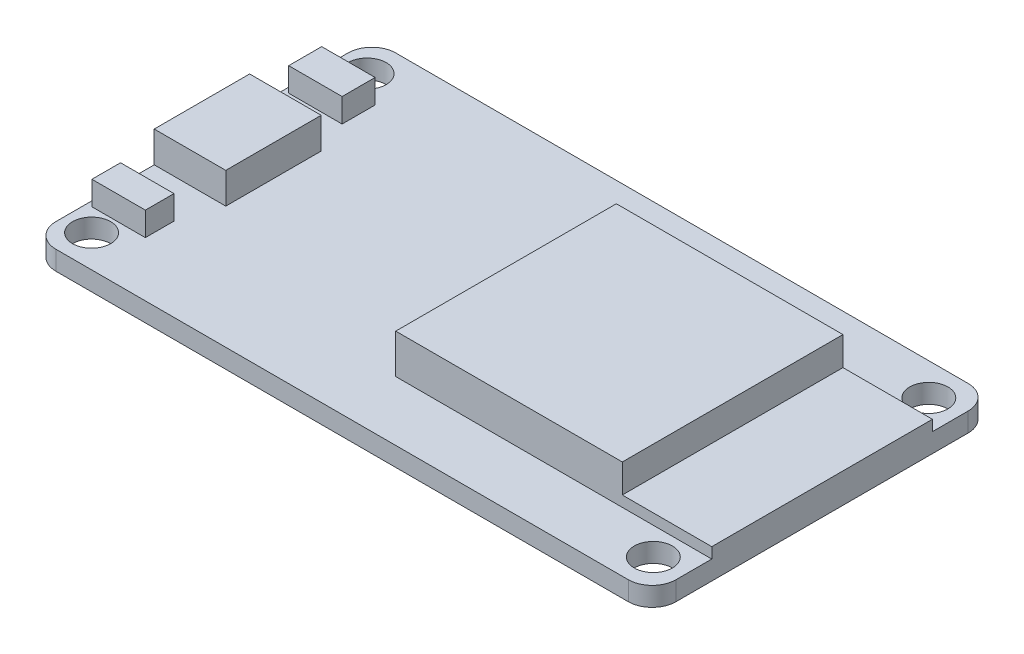
SolidWorks part; units mm, degrees
ref_plane "Front Plane" through (0, 0, 0) normal (0, 0, 1) x (1, 0, 0)
ref_plane "Top Plane" through (0, 0, 0) normal (0, 1, 0) x (1, 0, 0)
ref_plane "Right Plane" through (0, 0, 0) normal (1, 0, 0) x (0, 0, -1)
sketch "Sketch1" plane through (0, 0, 0) normal (0, 1, 0) x (1, 0, 0)
  line L1 (26, -14.25) -> (-26, -14.25)
  line L2 (26, -14.25) -> (26, 14.25)
  line L3 (26, 14.25) -> (-26, 14.25)
  line L4 (-26, -14.25) -> (-26, 14.25)
  line L5 (26, -14.25) -> (-26, 14.25) construction
  line L6 (26, 14.25) -> (-26, -14.25) construction
  line L7 (-23.7, -11.55) -> (23.4, -11.55) construction
  line L8 (-23.7, -11.55) -> (-23.7, 11.55) construction
  line L9 (-23.7, 11.55) -> (23.4, 11.55) construction
  line L10 (23.4, -11.55) -> (23.4, 11.55) construction
  line L11 (-23.7, -11.55) -> (23.4, 11.55) construction
  line L12 (-23.7, 11.55) -> (23.4, -11.55) construction
  circle A0 centre (-23.7, 11.55) radius 1.6
  circle A1 centre (-23.7, -11.55) radius 1.6
  circle A2 centre (23.4, 11.55) radius 1.6
  circle A3 centre (23.4, -11.55) radius 1.6
  point P0 (0, 0)
  point P10 (-0.15, 0)
  point P15 (0, 0)
  point P16 (0, 0)
  point P17 (0, 0)
  point P18 (-5.9824, 0)
  dimension "D3" = 3.2
  dimension "D1" = 52
  dimension "D2" = 28.5
  dimension "D4" = 2.3
  dimension "D5" = 2.6
  dimension "D6" = 2.7
extrude "Boss-Extrude1" add sketch "Sketch1" along normal blind 1.6
fillet "Fillet1" radius 2 4 edges at (26, 0.8, -14.25) (26, 0.8, 14.25) (-26, 0.8, -14.25) (-26, 0.8, 14.25)
sketch "Sketch2" plane through (0, 1.6, 0) normal (0, 1, 0) x (1, 0, 0)
  line L0 (-26, 12.25) -> (-26, -12.25) construction
  line L1 (-26, -4) -> (-20, -4)
  line L2 (-26, -4) -> (-26, 4)
  line L3 (-26, 4) -> (-20, 4)
  line L4 (-20, -4) -> (-20, 4)
  point P6 (-26, 3.826)
  point P7 (-26, 0)
  point P8 (-26, 0)
  dimension "D1" = 8
  dimension "D2" = 6
extrude "Boss-Extrude2" add sketch "Sketch2" along normal blind 2.6
sketch "Sketch3" plane through (0, 1.6, 0) normal (0, 1, 0) x (1, 0, 0)
  line L0 (26, -12.25) -> (26, 12.25) construction
  line L1 (26, -9.25) -> (-0.5, -9.25)
  line L2 (26, -9.25) -> (26, 9.25)
  line L3 (26, 9.25) -> (-0.5, 9.25)
  line L4 (-0.5, -9.25) -> (-0.5, 9.25)
  point P6 (26, 0)
  point P7 (26, 0)
  dimension "D1" = 18.5
  dimension "D2" = 26.5
extrude "Boss-Extrude3" add sketch "Sketch3" along normal blind 0.9
sketch "Sketch4" plane through (0, 2.5, 0) normal (0, 1, 0) x (1, 0, 0)
  line L0 (-0.5, -9.25) -> (26, -9.25) construction
  line L1 (-0.5, 9.25) -> (18.5, 9.25)
  line L2 (-0.5, 9.25) -> (-0.5, -9.25)
  line L3 (-0.5, -9.25) -> (18.5, -9.25)
  line L4 (18.5, 9.25) -> (18.5, -9.25)
  dimension "D1" = 19
extrude "Boss-Extrude4" add sketch "Sketch4" along normal blind 2.4
sketch "Sketch5" plane through (0, 1.6, 0) normal (0, 1, 0) x (1, 0, 0)
  line L1 (-25.5638, 9.6062) -> (-21.0835, 9.6062)
  line L2 (-25.5638, 9.6062) -> (-25.5638, 6.839)
  line L3 (-25.5638, 6.839) -> (-21.0835, 6.839)
  line L4 (-21.0835, 9.6062) -> (-21.0835, 6.839)
  line L5 (-25.5638, -7.2606) -> (-21.0835, -7.2606)
  line L6 (-25.5638, -7.2606) -> (-25.5638, -9.6589)
  line L7 (-25.5638, -9.6589) -> (-21.0835, -9.6589)
  line L8 (-21.0835, -7.2606) -> (-21.0835, -9.6589)
extrude "Boss-Extrude5" add sketch "Sketch5" along normal blind 2
